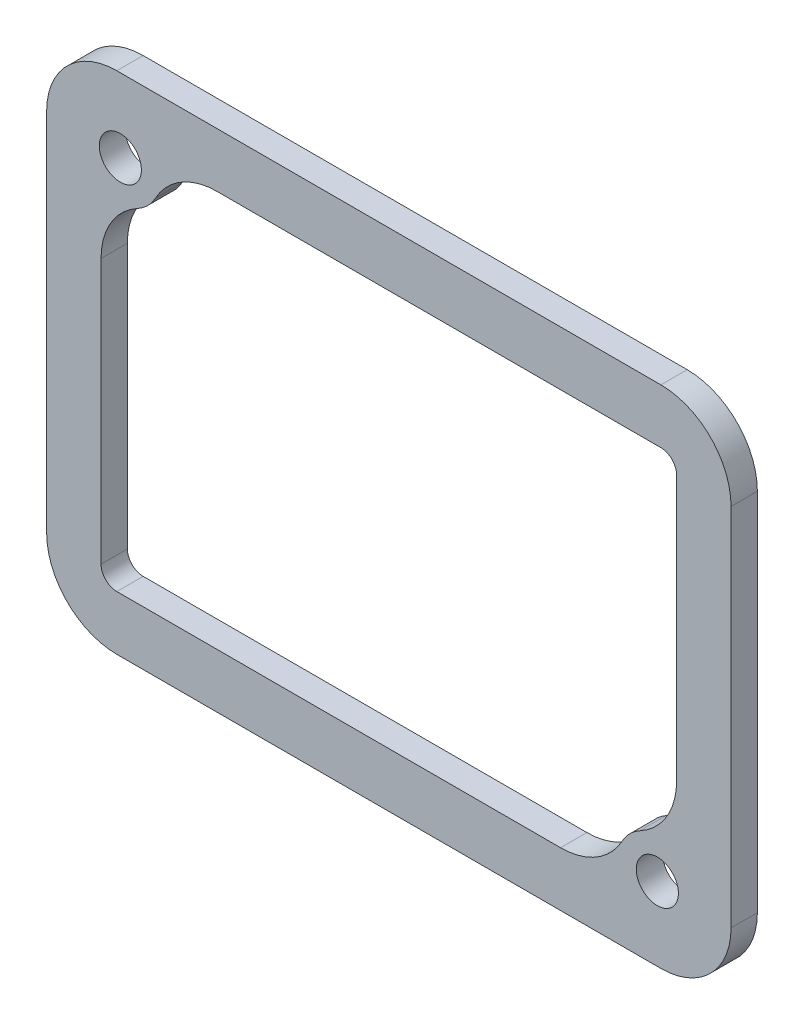
SolidWorks part; units mm, degrees
ref_plane "Ebene vorne" through (0, 0, 0) normal (0, 0, 1) x (1, 0, 0)
ref_plane "Ebene oben" through (0, 0, 0) normal (0, 1, 0) x (1, 0, 0)
ref_plane "Ebene rechts" through (0, 0, 0) normal (1, 0, 0) x (0, 0, -1)
sketch "Skizze1" plane through (0, 0, 0) normal (0, 0, 1) x (1, 0, 0)
  line L1 (15.5, -14.4) -> (-15.5, -14.4)
  line L2 (19.5, -10.4) -> (19.5, 10.4)
  line L3 (15.5, 14.4) -> (-15.5, 14.4)
  line L4 (-19.5, -10.4) -> (-19.5, 10.4)
  line L5 (19.5, -14.4) -> (-19.5, 14.4) construction
  line L6 (19.5, 14.4) -> (-19.5, -14.4) construction
  arc A0 (-15.5, -14.4) -> (-19.5, -10.4) centre (-15.5, -10.4) cw
  arc A1 (15.5, -14.4) -> (19.5, -10.4) centre (15.5, -10.4) ccw
  arc A2 (19.5, 10.4) -> (15.5, 14.4) centre (15.5, 10.4) ccw
  arc A3 (-15.5, 14.4) -> (-19.5, 10.4) centre (-15.5, 10.4) ccw
  point P0 (0, 0)
  dimension "D3" = 4
  dimension "D1" = 28.8
  dimension "D2" = 39
extrude "Aufsatz-Linear austragen1" add sketch "Skizze1" along normal blind 1.5
sketch "Skizze2" plane through (0, 0, 1.5) normal (0, 0, 1) x (1, 0, 0)
  line L0 (15.5, 11.3) -> (-9.7869, 11.3)
  line L1 (-16.4, 4.6869) -> (-16.4, -10.4)
  line L2 (-15.5, -11.3) -> (9.7869, -11.3)
  line L3 (16.4, -4.6869) -> (16.4, 10.4)
  line L4 (15.5, 11.3) -> (-15.5, 11.3) construction
  line L5 (-16.4, 10.4) -> (-16.4, -10.4) construction
  line L6 (15.5464, 10.4311) -> (-15.5464, -10.4311) construction
  line L7 (16.4, -10.4) -> (16.4, 10.4) construction
  line L8 (-15.5, -11.3) -> (15.5, -11.3) construction
  line L10 (-15.5, -12.3) -> (15.5, -12.3)
  line L11 (17.4, -10.4) -> (17.4, 10.4)
  line L12 (15.5, 12.3) -> (-15.5, 12.3)
  line L13 (-17.4, 10.4) -> (-17.4, -10.4)
  line L14 (-15.5, -12.3) -> (15.5, -12.3) construction
  line L15 (17.4, -10.4) -> (17.4, 10.4) construction
  line L16 (15.5, 12.3) -> (-15.5, 12.3) construction
  line L17 (-17.4, 10.4) -> (-17.4, -10.4) construction
  arc A1 (-16.4, -10.4) -> (-15.5, -11.3) centre (-15.5, -10.4) ccw
  arc A3 (16.4, 10.4) -> (15.5, 11.3) centre (15.5, 10.4) ccw
  arc A4 (-14.3077, 8.2026) -> (-13.3026, 9.2077) centre (-15.5, 10.4) ccw
  arc A5 (-14.3077, 8.2026) -> (-16.4, 4.6869) centre (-12.4, 4.6869) ccw
  arc A6 (-13.3026, 9.2077) -> (-9.7869, 11.3) centre (-9.7869, 7.3) cw
  circle A7 centre (-15.3, 10.2) radius 1.6 construction
  arc A8 (14.3077, -8.2026) -> (13.3026, -9.2077) centre (15.5, -10.4) ccw
  arc A9 (14.3077, -8.2026) -> (16.4, -4.6869) centre (12.4, -4.6869) ccw
  arc A10 (13.3026, -9.2077) -> (9.7869, -11.3) centre (9.7869, -7.3) cw
  circle A11 centre (15.3, -10.2) radius 1.6 construction
  arc A12 (-17.4, -10.4) -> (-15.5, -12.3) centre (-15.5, -10.4) ccw
  arc A13 (15.5, -12.3) -> (17.4, -10.4) centre (15.5, -10.4) ccw
  arc A14 (17.4, 10.4) -> (15.5, 12.3) centre (15.5, 10.4) ccw
  arc A15 (-15.5, 12.3) -> (-17.4, 10.4) centre (-15.5, 10.4) ccw
  arc A16 (-17.4, -10.4) -> (-15.5, -12.3) centre (-15.5, -10.4) ccw construction
  arc A17 (15.5, -12.3) -> (17.4, -10.4) centre (15.5, -10.4) ccw construction
  arc A18 (17.4, 10.4) -> (15.5, 12.3) centre (15.5, 10.4) ccw construction
  arc A19 (-15.5, 12.3) -> (-17.4, 10.4) centre (-15.5, 10.4) ccw construction
  arc A20 (-15.5, 11.3) -> (-16.4, 10.4) centre (-15.5, 10.4) ccw construction
  arc A21 (15.5, -11.3) -> (16.4, -10.4) centre (15.5, -10.4) ccw construction
  dimension "D3" = 5
  dimension "D4" = 4
  dimension "D5" = 3.2
  dimension "D6" = 5
  dimension "D7" = 4
  dimension "D10" = 3.2
  dimension "D8" = 2.1
  dimension "D9" = 2.1
  dimension "D11" = 2.1
  dimension "D12" = 2.1
  dimension "D1" = 2.1
  dimension "D2" = 1
extrude "Schnitt-Linear austragen3" cut sketch "Skizze2" against normal through all
sketch "Skizze8" plane through (0, 0, 1.5) normal (0, 0, 1) x (1, 0, 0)
  circle A4 centre (-15.3, 10.2) radius 1.2
  circle A5 centre (15.3, -10.2) radius 1.2
  dimension "D1" = 2.4
  dimension "D2" = 2.4
extrude "Schnitt-Linear austragen4" cut sketch "Skizze8" against normal through all
equation "\"D10@Skizze2\"=\"D5@Skizze2\""
